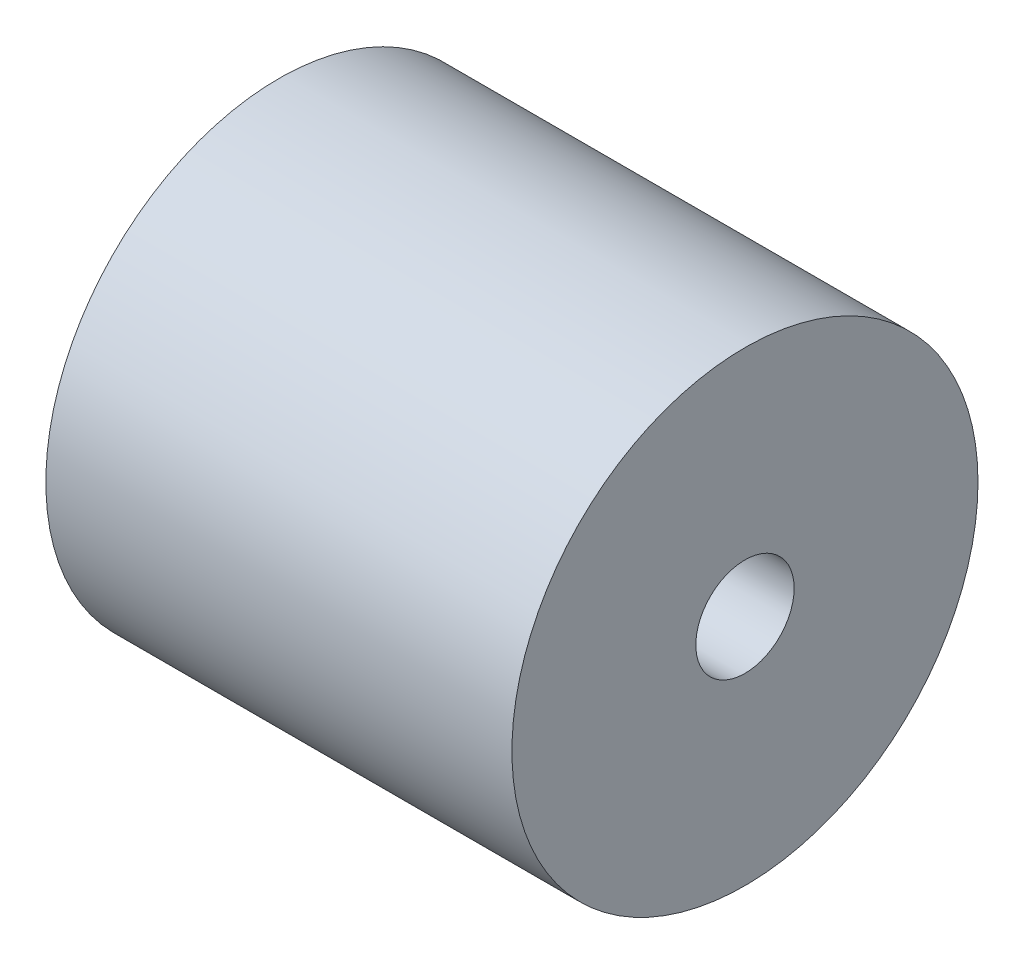
SolidWorks part; units mm, degrees
ref_plane "Front Plane" through (0, 0, 0) normal (0, 0, 1) x (1, 0, 0)
ref_plane "Top Plane" through (0, 0, 0) normal (0, 1, 0) x (1, 0, 0)
ref_plane "Right Plane" through (0, 0, 0) normal (1, 0, 0) x (0, 0, -1)
sketch "Sketch1" plane through (0, 0, 0) normal (1, 0, 0) x (0, 0, -1)
  circle A0 centre (0, 0) radius 25
  dimension "D1" = 50
extrude "Boss-Extrude1" add sketch "Sketch1" along normal blind 50
sketch "Sketch2" plane through (0, 0, 0) normal (0, 1, 0) x (1, 0, 0)
  line L0 (50, 0) -> (0, 0) construction
  line L1 (50, -25) -> (50, 25) construction
  line L2 (50, 0) -> (37.5, 0)
  line L3 (42, 5.275) -> (50, 5.275)
  line L4 (42, 5.275) -> (42, -5.275)
  line L5 (42, -5.275) -> (50, -5.275)
  line L6 (50, 5.275) -> (50, -5.275)
  line L7 (42, 5.275) -> (50, -5.275) construction
  line L8 (42, -5.275) -> (50, 5.275) construction
  line L9 (39.85, 4.675) -> (42, 4.675)
  line L10 (39.85, 4.675) -> (39.85, -4.675)
  line L11 (39.85, -4.675) -> (42, -4.675)
  line L12 (42, 4.675) -> (42, -4.675)
  line L13 (39.85, 4.675) -> (42, -4.675) construction
  line L14 (39.85, -4.675) -> (42, 4.675) construction
  line L15 (37.5, -3.225) -> (39.85, -3.225)
  line L16 (37.5, -3.225) -> (37.5, 3.225)
  line L17 (37.5, 3.225) -> (39.85, 3.225)
  line L18 (39.85, -3.225) -> (39.85, 3.225)
  line L19 (37.5, -3.225) -> (39.85, 3.225) construction
  line L20 (37.5, 3.225) -> (39.85, -3.225) construction
  point P5 (46, 0)
  point P10 (40.925, 0)
  point P15 (38.675, 0)
  dimension "D1" = 10.55
  dimension "D2" = 8
  dimension "D3" = 9.35
  dimension "D4" = 10.15
  dimension "D5" = 6.45
  dimension "D6" = 12.5
revolve "Cut-Revolve3" cut sketch "Sketch2" angle 360 about L0
